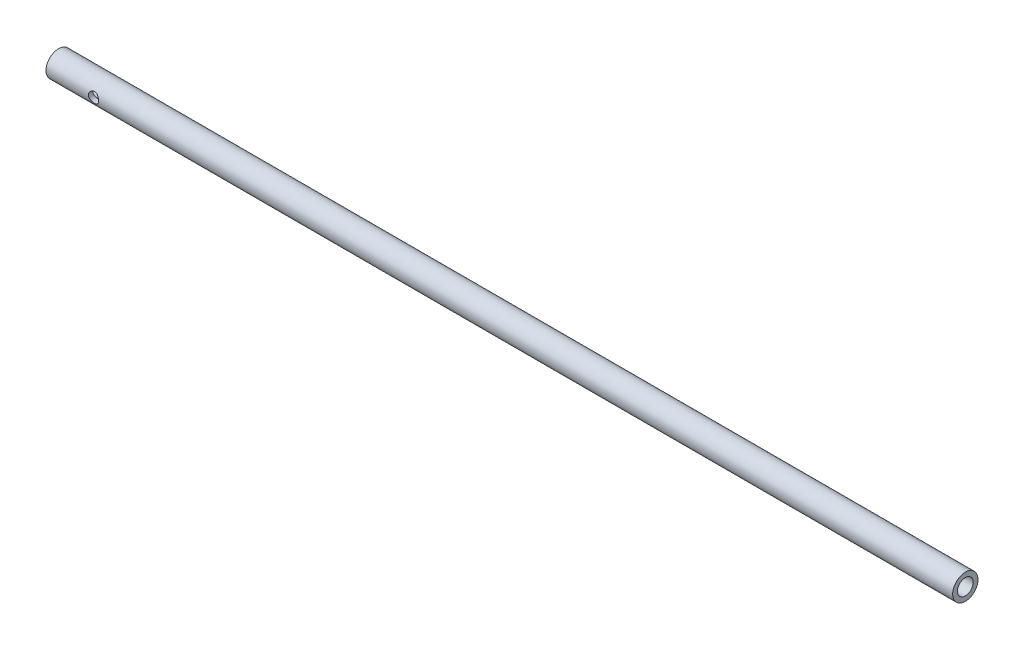
SolidWorks part; units mm, degrees
ref_plane "Front Plane" through (0, 0, 0) normal (0, 0, 1) x (1, 0, 0)
ref_plane "Top Plane" through (0, 0, 0) normal (0, 1, 0) x (1, 0, 0)
ref_plane "Right Plane" through (0, 0, 0) normal (1, 0, 0) x (0, 0, -1)
sketch "Sketch1" plane through (0, 0, 0) normal (1, 0, 0) x (0, 0, -1)
  circle A0 centre (0, 0) radius 16
  circle A1 centre (0, 0) radius 10
  dimension "D1" = 32
  dimension "D2" = 20
extrude "Boss-Extrude1" add sketch "Sketch1" against normal blind 920 and the other way blind 226
sketch "Sketch2" plane through (0, 0, 0) normal (0, 0, 1) x (1, 0, 0)
  line L0 (-920, 16) -> (-920, -16) construction
  line L1 (-920, 0) -> (-604.8317, 0) construction
  circle A0 centre (-860, 0) radius 6.5
  dimension "D1" = 13
  dimension "D2" = 60
extrude "Cut-Extrude1" cut sketch "Sketch2" against normal mid plane 59
